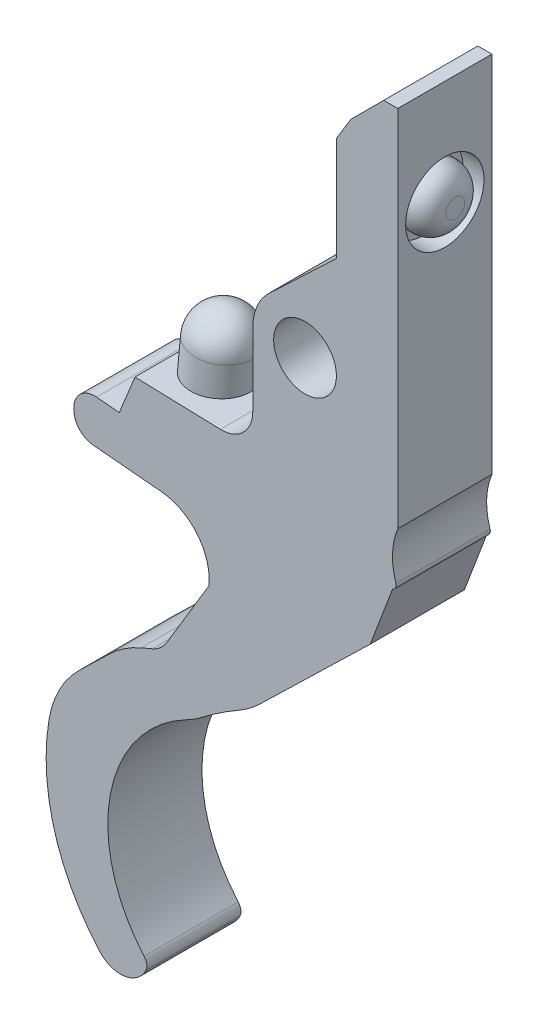
SolidWorks part; units mm, degrees
ref_plane "정면" through (0, 0, 0) normal (0, 0, 1) x (1, 0, 0)
ref_plane "윗면" through (0, 0, 0) normal (0, 1, 0) x (1, 0, 0)
ref_plane "우측면" through (0, 0, 0) normal (1, 0, 0) x (0, 0, -1)
sketch "스케치1" plane through (0, 0, 0) normal (0, 0, 1) x (1, 0, 0)
  line L0 (7.5189, 25.0781) -> (8.8664, 25.0781)
  line L1 (7.5189, 25.0781) -> (4.3842, 21.9434)
  line L2 (8.8664, 25.0781) -> (8.8664, -9.7282)
  line L3 (-5, 0) -> (-5, -10.0714)
  line L4 (-17.7666, -13.4266) -> (-19.9405, -13.2288)
  line L5 (2.9878, 19.65) -> (2.9878, 17.6612)
  line L6 (-20.2877, -17.3633) -> (-13.717, -17.9611)
  line L7 (2.9878, 17.6612) -> (2.9878, 9.7088)
  line L8 (2.9878, 9.7088) -> (-3.1847, 3.8546)
  line L9 (8.3701, -14.9782) -> (6.2381, -20.6005)
  line L10 (2.2148, 21.9434) -> (17.8049, 21.9434) construction
  line L11 (4.3842, 21.9434) -> (2.9878, 19.65)
  line L12 (6.2381, -20.6005) -> (-4.3386, -30.8592)
  line L13 (-5, -10.0714) -> (-16.2648, -9.7282)
  line L14 (-16.2648, -9.7282) -> (-17.7666, -13.4266)
  line L16 (-9.201, -23.497) -> (-13.2181, -30.1935)
  line L17 (-18.7012, -33.8794) -> (-21.5874, -36.6789)
  line L18 (-15.6804, -31.8671) -> (-14.6082, -31.4073)
  circle A0 centre (0, 0) radius 3
  circle A1 centre (0, 0) radius 5
  arc A2 (-6.3376, -32.3623) -> (-4.3386, -30.8592) centre (-11.3009, -23.681) ccw
  arc A3 (-6.3376, -32.3623) -> (-9.8499, -34.7011) centre (9.0543, -59.2837) ccw
  arc A4 (-24.4913, -42.2266) -> (-19.6524, -58.9718) centre (-4.5193, -45.5271) ccw
  arc A5 (-22.1027, -15.4958) -> (-20.2877, -17.3633) centre (-20.1065, -15.3716) ccw
  arc A6 (-19.9405, -13.2288) -> (-22.1027, -15.4958) centre (-20.1217, -15.2206) ccw
  arc A7 (8.8664, -9.7282) -> (8.6919, -14.3466) centre (15.0215, -12.2733) ccw
  arc A8 (8.6919, -14.3466) -> (8.3701, -14.9782) centre (8.2168, -14.5023) cw
  arc A9 (-13.717, -17.9611) -> (-9.201, -23.497) centre (-14.17, -22.9405) cw
  arc A10 (-11.3342, -35.6471) -> (-9.8499, -34.7011) centre (-15.9459, -26.774) ccw
  arc A11 (-21.5874, -36.6789) -> (-24.4913, -42.2266) centre (-14.6251, -43.857) ccw
  arc A12 (-19.6524, -58.9718) -> (-15.2319, -58.3761) centre (-17.6426, -57.1863) ccw
  arc A13 (-15.3951, -57.2539) -> (-11.3342, -35.6471) centre (-4.8916, -48.043) cw
  arc A14 (-15.2319, -58.3761) -> (-15.3951, -57.2539) centre (-16.1286, -57.9335) ccw
  arc A15 (-18.7012, -33.8794) -> (-15.6804, -31.8671) centre (-11.7388, -41.0576) cw
  arc A16 (-14.6082, -31.4073) -> (-13.2181, -30.1935) centre (-15.7907, -28.6502) ccw
  dimension "D1" = 6
  dimension "D2" = 10
  dimension "D4" = 2
  dimension "D5" = 0.5
  dimension "D6" = 5
  dimension "D7" = 10
  dimension "D8" = 3
  dimension "D9" = 1
  dimension "D3" = 45
extrude "보스-돌출1" add sketch "스케치1" along normal blind 9
sketch "스케치2" plane through (8.8664, 0, 0) normal (1, 0, 0) x (0, 0, -1)
  line L0 (-9, 25.0781) -> (0, 25.0781) construction
  circle A0 centre (-4.5, 15.0781) radius 3.75
  dimension "D1" = 7.5
  dimension "D2" = 10
extrude "컷-돌출1" cut sketch "스케치2" against normal blind 2
sketch "스케치3" plane through (6.8664, 0, 0) normal (1, 0, 0) x (0, 0, -1)
  circle A0 centre (-4.5, 15.0781) radius 2.9
  dimension "D1" = 5.8
extrude "보스-돌출2" add sketch "스케치3" along normal blind 3
fillet "필렛1" radius 2 1 edges at (9.8664, 17.9781, 4.5)
sketch "스케치4" plane through (-1.3573, -14.9194, 0) normal (0.0906, 0.9959, 0) x (0.9959, -0.0906, 0)
  line L0 (-3.6578, -9) -> (-3.6578, 0) construction
  circle A0 centre (-11.6578, -4.5) radius 2.9
  point P2 (-3.6578, -4.5)
  dimension "D1" = 5.8
  dimension "D2" = 8
extrude "보스-돌출3" add sketch "스케치4" along normal blind 10
fillet "필렛2" radius 2.9 1 edges at (-14.9492, -3.6416, 4.5)
fillet "필렛3" radius 3 1 edges at (-5, -10.0714, 4.5)
